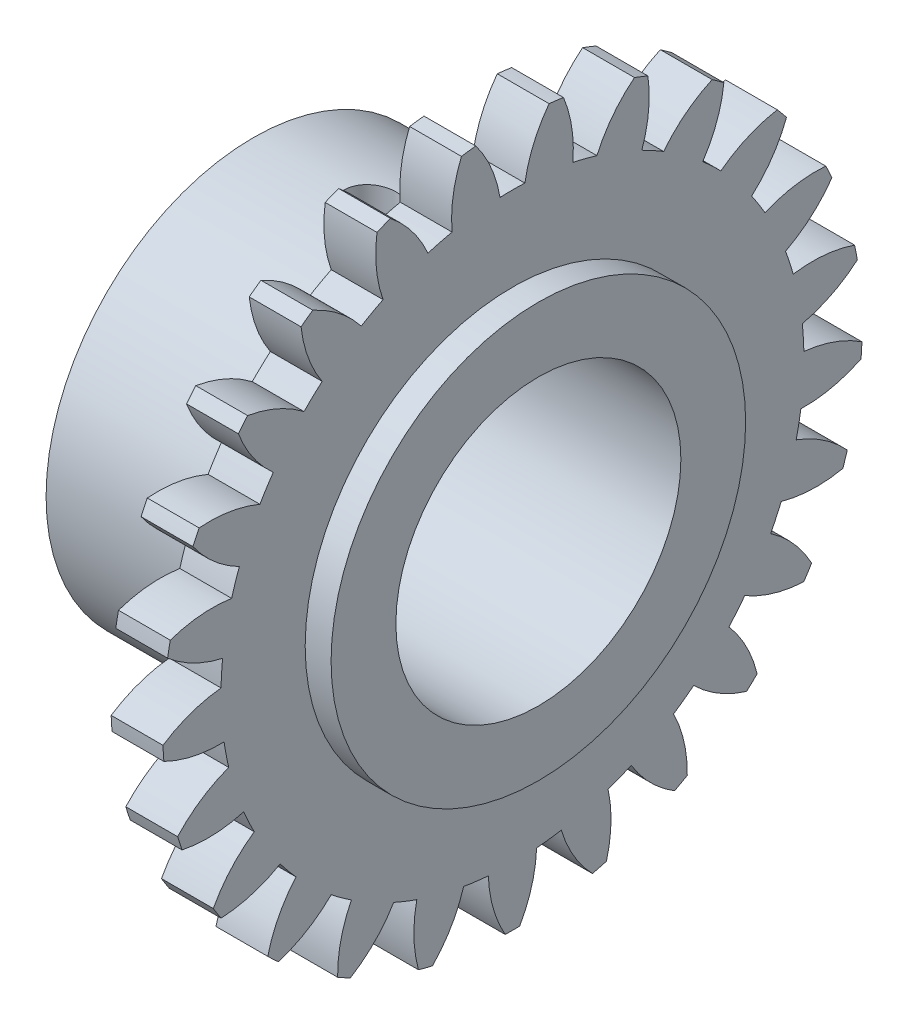
SolidWorks part; units mm, degrees
material "Alliage de zinc AC41A, brut"
ref_plane "Plane1" through (0, 0, 0) normal (0, 0, 1) x (1, 0, 0)
ref_plane "Plane2" through (0, 0, 0) normal (0, 1, 0) x (1, 0, 0)
ref_plane "Plane3" through (0, 0, 0) normal (1, 0, 0) x (0, 0, -1)
sketch "HoldingSke" plane through (0, 0, 0) normal (0, 1, 0) x (1, 0, 0)
  line L0 (0, 0) -> (0.9063, -0.4226)
  line L1 (-15, 0) -> (100, 0) construction
  line L2 (0, 0) -> (-2.1039, 2.3779)
  line L3 (0, 0) -> (-11.863, 4.5341)
  line L4 (0, 0) -> (7.8269, 3.6497)
  line L5 (0, 0) -> (-46.8476, -17.4728)
  line L6 (0, 0) -> (-1.6579, -1.1186)
  line L7 (-2.1039, 2.3779) -> (8.6586, 51.2059)
  line L8 (-76.2, 54.61) -> (-75.9, 54.61)
  line L9 (-71.009, 38.7566) -> (-53.1078, 45.2721)
  line L10 (-76.2, 71.12) -> (104.1128, 71.12)
  line L11 (0, 0) -> (-2, 0)
  line L12 (-76.2, 101.6) -> (-76.162, 101.6)
  line L13 (24.9733, 27.94) -> (52.9518, 28.4284)
  line L14 (24.9733, 27.94) -> (24.9743, 27.94)
  line L15 (24.9733, 27.94) -> (100.4006, 29.5858)
  line L16 (-63.627, -1) -> (-12.827, -1)
  circle A0 centre (0, 0) radius 1
  circle A1 centre (0, 0) radius 11.249
  circle A2 centre (0, 0) radius 37.5
  circle A3 centre (0, 0) radius 5.5
  dimension "MHD" = 22.498
  dimension "Hub_dia" = 75
  dimension "Bore" = 2
  dimension "MBD" = 11
  dimension "Num_teeth" = 25
  dimension "Pitch" = 1
  dimension "Overall_len" = 50
  dimension "Show_teeth" = 25
  dimension "Thickness" = 2
  dimension "OAL" = 50.0001
  dimension "T_dim" = 0.3
  dimension "Ap" = 20
  dimension "H" = 19.05
  dimension "Pitch_radius" = 180.3128
  dimension "Width" = 2
  dimension "Backlash" = 0.038
  dimension "Addendum_fac" = 1
  dimension "Dedendum_fac" = 1.25
  dimension "Clearance_fac" = 0.25
  dimension "Dedendum_add" = 0.001
  dimension "Module" = 1
sketch "BasProSke" plane through (0, 0, 0) normal (0, 1, 0) x (1, 0, 0)
  line L0 (-10, 0) -> (60, 0) construction
  line L1 (0, 0) -> (0, 13.5)
  line L2 (0, 0) -> (2, 0)
  line L3 (2, 0) -> (2, 13.5)
  line L4 (2, 13.5) -> (0, 13.5)
  dimension "Thickness" = 2
  dimension "Diameter" = 27
revolve "Base-Revolve" add sketch "BasProSke" angle 360 about L0
sketch "TooCutSke" plane through (0, 0, 0) normal (1, 0, 0) x (0, 0, -1)
  line L1 (0, 0) -> (0, 107) construction
  line L2 (0, 0) -> (-0.8514, 12.471) construction
  line L3 (0, 0) -> (-3.1282, 24.7619) construction
  line L4 (-0.8514, 12.471) -> (-1.5641, 12.3809) construction
  arc A0 (0.4801, 11.2388) -> (-0.4801, 11.2388) centre (0, 0) ccw
  arc A1 (1.4322, 13.4494) -> (-1.4322, 13.4494) centre (0, 0) ccw
  circle A2 centre (0, 0) radius 12.5 construction
  circle A3 centre (0, 0) radius 11.7462 construction
  arc A4 (-0.4801, 11.2388) -> (-1.4322, 13.4494) centre (-5.4133, 10.4244) ccw
  arc A5 (1.4322, 13.4494) -> (0.4801, 11.2388) centre (5.4133, 10.4244) ccw
  dimension "Root_dia" = 22.498
  dimension "Overcut_dia" = 27.0508
  dimension "Pitch_dia" = 25
  dimension "Base_dia" = 23.4923
  dimension "Flank_rad" = 5
  dimension "Half_ang" = 7.2
  dimension "Half_CT" = 0.7184
extrude "ToothCut" cut sketch "TooCutSke" along normal through all
fillet "Breaks" [suppressed] radius 0.02
fillet "RootFillets" [suppressed] radius 0.251
pattern_circular "TeethCuts" count 25 every 14.4 about axis through (-10, 0, 0) along (1, 0, 0) of "ToothCut", "RootFillets", "Breaks"
sketch "HubNeaOneSke" plane through (0, 0, 0) normal (-1, 0, 0) x (0, 0, 1)
  circle A0 centre (0, 0) radius 11.249
  dimension "Diameter" = 22.498
extrude "HubNearOne" [suppressed] add sketch "HubNeaOneSke" along normal blind 48.0001
sketch "HubNeaBotSke" plane through (0, 0, 0) normal (-1, 0, 0) x (0, 0, 1)
  circle A0 centre (0, 0) radius 11.249
  dimension "Diameter" = 22.498
extrude "HubNearBoth" [suppressed] add sketch "HubNeaBotSke" along normal blind 24
ref_plane "FarPln" through (2, 0, 0) normal (1, 0, 0) x (0, 0, -1)
sketch "HubFarSke" plane through (2, 0, 0) normal (1, 0, 0) x (0, 0, -1)
  circle A0 centre (0, 0) radius 11.249
  dimension "Diameter" = 22.498
extrude "HubFar" [suppressed] add sketch "HubFarSke" along normal blind 24
sketch "BorSke" plane through (0, 0, 0) normal (1, 0, 0) x (0, 0, -1)
  circle A0 centre (0, 0) radius 5.5
  dimension "Diameter" = 11
extrude "Bore" cut sketch "BorSke" along normal mid plane 100.0001
sketch "KeySke" plane through (0, 0, 0) normal (1, 0, 0) x (0, 0, -1)
  line L0 (-0.4, 0) -> (-0.4, 5.8)
  line L1 (-0.4, 5.8) -> (0.4, 5.8)
  line L2 (0.4, 5.8) -> (0.4, 0)
  line L3 (0, 0) -> (0, 34) construction
  line L4 (-0.4, 0) -> (0.4, 0)
  dimension "Offset" = 5.8
  dimension "Width" = 0.8
extrude "Keyway" [suppressed] cut sketch "KeySke" along normal mid plane 100.0001
pattern_circular "Keyway2" [suppressed] count 2 every 90 about axis through (-10, 0, 0) along (1, 0, 0)
sketch "Esquisse1" plane through (2, 0, 0) normal (1, 0, 0) x (0, 0, -1)
  circle A0 centre (0, 0) radius 5.5
  circle A1 centre (0, 0) radius 8
  dimension "D1" = 11
  dimension "D2" = 16
extrude "Boss.-Extru.1" add sketch "Esquisse1" along normal blind 1
sketch "Esquisse2" plane through (0, 0, 0) normal (-1, 0, 0) x (0, 0, 1)
  circle A0 centre (0, 0) radius 8
  circle A1 centre (0, 0) radius 5.5
  dimension "D1" = 16
  dimension "D2" = 11
extrude "Boss.-Extru.2" add sketch "Esquisse2" along normal blind 8
sketch "Esquisse7" plane through (0, 0, 0) normal (0, 1, 0) x (1, 0, 0)
  line L0 (0, 8) -> (0, -8) construction
  point P0 (-3.5, 0)
  dimension "D1" = 3.5
hole_wizard "Diamètre du perçage Ø2.0 (2)1" positions "Esquisse7" profile "Esquisse4" hole size "Ø2.0" standard "ISO"
sketch "Esquisse4" plane through (-3.5, 0, 0) normal (1, 0, 0) x (0, 0, -1)
  line L0 (0, 0) -> (0, 13.4257)
  line L1 (0, 13.4257) -> (1, 13.4257)
  line L2 (1, 13.4257) -> (1, 0)
  line L5 (1, 0) -> (0, 0)
  line L11 (0, -6.35) -> (0, 107.95) construction
  dimension "Diamètre du perçage jusqu'au prochain" = 2
  dimension "Profondeur du perçage jusqu'au prochain" = 13.4257
cosmetic thread "Représentation de filetage1" parameters "D2"=3
equation "' \"Module@HoldingSke\" = 6.35"
equation "' \"Num_teeth@HoldingSke\" = 12"
equation "' \"Ap@HoldingSke\" =  20"
equation "' \"Ap@HoldingSke\" = 20"
equation "' \"Width@HoldingSke\" = 0.5 * 25.4"
equation "' \"Hub_dia@HoldingSke\"= 1 * 25.4"
equation "' \"Hub_dia@HoldingSke\" = 1 * 25.4"
equation "' \"Overall_len@HoldingSke\" = 1.0 * 25.4"
equation "' \"Bore@HoldingSke\" = 0.75 * 25.4"
equation "' \"T_dim@HoldingSke\" = 0.1 * 25.4"
equation "' \"Width@KeySke\" = 0.25 * 25.4"
equation "' \"Show_teeth@HoldingSke\" = 13"
equation "' \"Backlash@HoldingSke\" = 0.009 * 25.4"
equation "' \"Addendum_fac@HoldingSke\" = 1.0"
equation "' \"Dedendum_fac@HoldingSke\" = 1.25"
equation "' \"Dedendum_add@HoldingSke\" = 0.00005 * 25.4"
equation "' \"Clearance_fac@HoldingSke\" = 0.25"
equation "\"Pitch@HoldingSke\" = 1 / \"Module@HoldingSke\""
equation "\"Overcut_dia@TooCutSke\" = (\"Num_teeth@HoldingSke\" + 2 * \"Addendum_fac@HoldingSke\") / \"Pitch@HoldingSke\" + 0.002 * 25.4"
equation "\"Pitch_dia@TooCutSke\" = \"Num_teeth@HoldingSke\" / \"Pitch@HoldingSke\""
equation "\"Base_dia@TooCutSke\" = \"Num_teeth@HoldingSke\" / \"Pitch@HoldingSke\" * cos((\"Ap@HoldingSke\"  * 3.14159265 / 180))"
equation "\"Root_dia@TooCutSke\" = (\"Num_teeth@HoldingSke\" + 2) / \"Pitch@HoldingSke\" - 2 * (\"Addendum_fac@HoldingSke\" + \"Dedendum_fac@HoldingSke\") / \"Pitch@HoldingSke\" - \"Dedendum_add@HoldingSke\" * 2"
equation "\"Half_ang@TooCutSke\" = 180 / \"Num_teeth@HoldingSke\""
equation "\"Half_CT@TooCutSke\" = \"Num_teeth@HoldingSke\" / \"Pitch@HoldingSke\" * sin((3.14159265 / 2 / \"Num_teeth@HoldingSke\")) / 2 - 7 * \"Backlash@HoldingSke\" / 4"
equation "\"Flank_rad@TooCutSke\" = \"Num_teeth@HoldingSke\" / \"Pitch@HoldingSke\" / 5"
equation "\"Radius@RootFillets\" = \"Clearance_fac@HoldingSke\" / \"Pitch@HoldingSke\" + \"Dedendum_add@HoldingSke\""
equation "\"Break_rad@Breaks\" = 0.02 / \"Pitch@HoldingSke\""
equation "\"Thickness@HoldingSke\" = \"Width@HoldingSke\""
equation "\"OAL@HoldingSke\" = \"Thickness@HoldingSke\""
equation "\"MHD@HoldingSke\" = (\"Num_teeth@HoldingSke\" + 2) / \"Pitch@HoldingSke\" - 2 * (\"Addendum_fac@HoldingSke\" + \"Dedendum_fac@HoldingSke\")  / \"Pitch@HoldingSke\" - \"Dedendum_add@HoldingSke\" * 2"
equation "\"MHD@HoldingSke\" = ((sgn( \"MHD@HoldingSke\" - \"Hub_dia@HoldingSke\" )-1)*( \"MHD@HoldingSke\" - \"Hub_dia@HoldingSke\" ))/-2+ \"Hub_dia@HoldingSke\""
equation "\"OAL@HoldingSke\" = ((sgn( \"OAL@HoldingSke\" - \"Overall_len@HoldingSke\" )+1)*( \"OAL@HoldingSke\" - \"Overall_len@HoldingSke\" ))/2 + \"Overall_len@HoldingSke\" + 0.000002 * 25.4"
equation "\"Num_teeth@TeethCuts\" = int( \"Show_teeth@HoldingSke\" ) + 1"
equation "\"Num_teeth@TeethCuts\" = ((sgn( \"Num_teeth@TeethCuts\" - \"Num_teeth@HoldingSke\" )-1)*( \"Num_teeth@TeethCuts\" - \"Num_teeth@HoldingSke\" ))/-2+ \"Num_teeth@HoldingSke\""
equation "\"Num_teeth@TeethCuts\" = ((sgn( \"Num_teeth@TeethCuts\" - 2.0)+1)*( \"Num_teeth@TeethCuts\" - 2.0))/2 +2.0"
equation "\"Angle@TeethCuts\" = 360.0 / \"Num_teeth@HoldingSke\""
equation "\"Diameter@BasProSke\" = (\"Num_teeth@HoldingSke\" + 2 * \"Addendum_fac@HoldingSke\") / \"Pitch@HoldingSke\""
equation "\"Thickness@BasProSke\"  = \"Thickness@HoldingSke\""
equation "' \"Fillet_rad@BasProSke\" =  \"Thickness@HoldingSke\" * 0.05"
equation "' \"Fillet_rad@BasProSke\" = \"Thickness@HoldingSke\" * 0.05"
equation "\"MHD@HoldingSke\" = ((sgn( \"MHD@HoldingSke\" - \"Root_dia@TooCutSke\" )-1)*( \"MHD@HoldingSke\" - \"Root_dia@TooCutSke\" ))/-2+ \"Root_dia@TooCutSke\""
equation "\"Diameter@HubNeaOneSke\" = \"MHD@HoldingSke\""
equation "\"Length@HubNearOne\" = \"OAL@HoldingSke\" - \"Thickness@BasProSke\""
equation "\"Diameter@HubNeaBotSke\" = \"MHD@HoldingSke\""
equation "\"Length@HubNearBoth\" = ( \"OAL@HoldingSke\" - \"Thickness@BasProSke\" ) / 2.0"
equation "\"Thickness@FarPln\" = \"Thickness@BasProSke\""
equation "\"Diameter@HubFarSke\" = \"MHD@HoldingSke\""
equation "\"Length@HubFar\" = ( \"OAL@HoldingSke\" - \"Thickness@BasProSke\" ) / 2.0"
equation "\"Diameter@BorSke\" = \"MBD@HoldingSke\""
equation "\"D1@Bore\" = \"OAL@HoldingSke\" * 2.0"
equation "\"D1@Keyway\" = \"OAL@HoldingSke\" * 2.0"
equation "\"Offset@KeySke\" = \"T_dim@HoldingSke\" + \"MBD@HoldingSke\" / 2.0"
